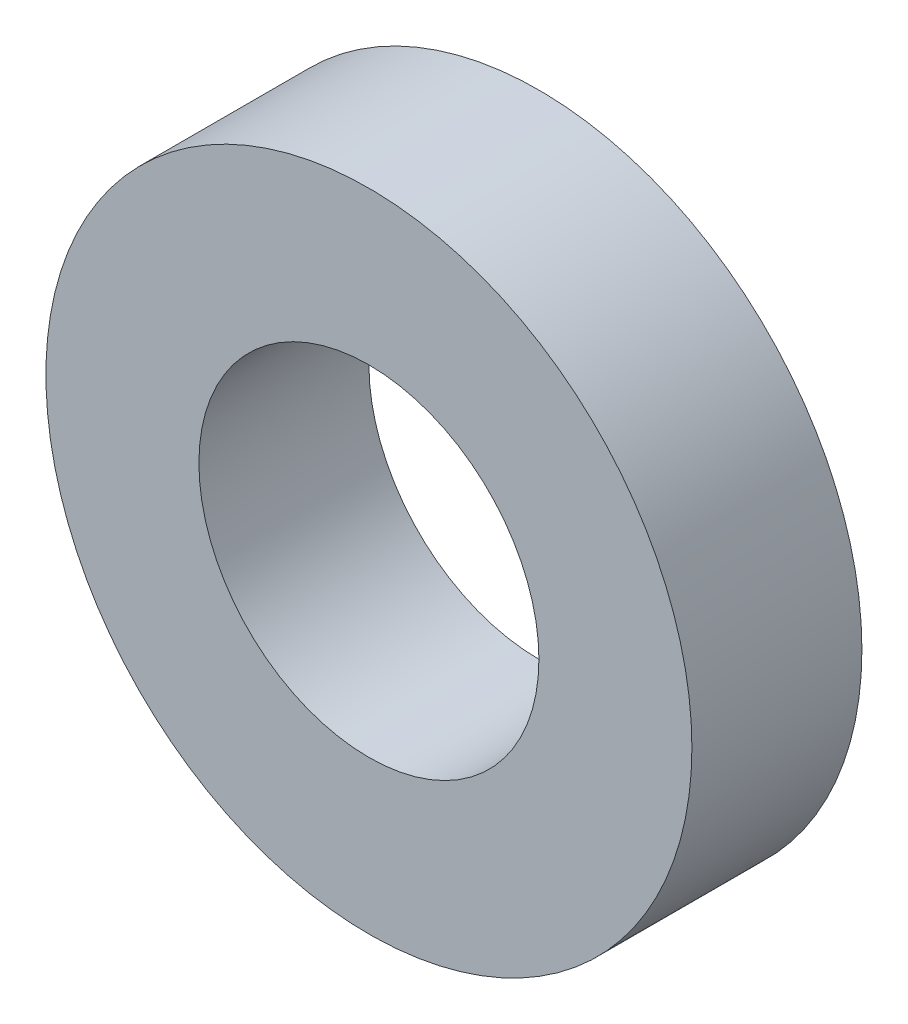
SolidWorks part; units mm, degrees
ref_plane "Front Plane" through (0, 0, 0) normal (0, 0, 1) x (1, 0, 0)
ref_plane "Top Plane" through (0, 0, 0) normal (0, 1, 0) x (1, 0, 0)
ref_plane "Right Plane" through (0, 0, 0) normal (1, 0, 0) x (0, 0, -1)
sketch "Sketch1" plane through (0, 0, 0) normal (0, 0, 1) x (1, 0, 0)
  circle A0 centre (0, 0) radius 9.5
  circle A1 centre (0, 0) radius 5
  dimension "D1" = 10
  dimension "D2" = 19
extrude "Boss-Extrude1" add sketch "Sketch1" along normal blind 5
